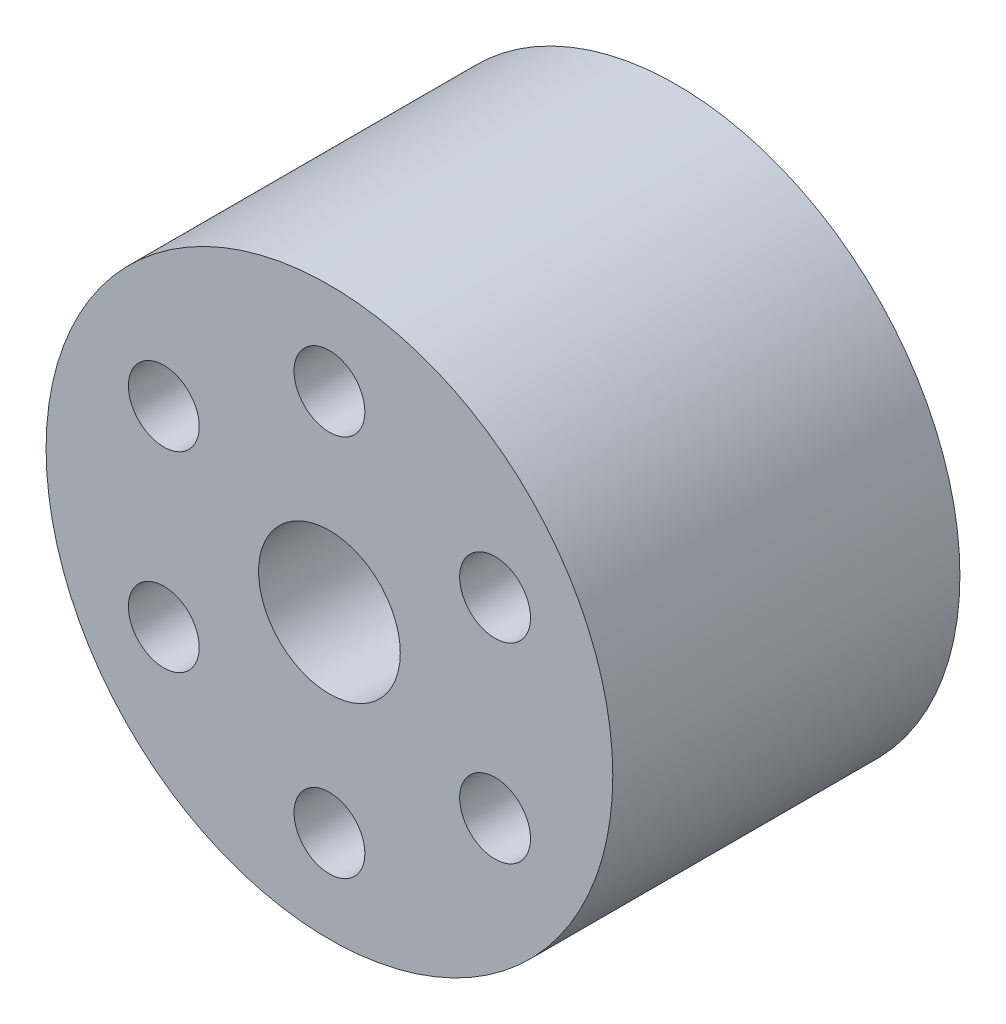
SolidWorks part; units mm, degrees
material "1060 합금"
ref_plane "정면" through (0, 0, 0) normal (0, 0, 1) x (1, 0, 0)
ref_plane "윗면" through (0, 0, 0) normal (0, 1, 0) x (1, 0, 0)
ref_plane "우측면" through (0, 0, 0) normal (1, 0, 0) x (0, 0, -1)
sketch "스케치1" plane through (0, 0, 0) normal (0, 0, 1) x (1, 0, 0)
  circle A0 centre (0, 0) radius 20
  dimension "D1" = 40
extrude "보스-돌출1" add sketch "스케치1" along normal blind 24.5
sketch "스케치2" plane through (0, 0, 24.5) normal (0, 0, 1) x (1, 0, 0)
  circle A0 centre (0, 0) radius 5
  dimension "D1" = 10
extrude "컷-돌출1" cut sketch "스케치2" against normal blind 10
sketch "스케치3" plane through (0, 0, 14.5) normal (0, 0, 1) x (1, 0, 0)
  circle A0 centre (0, 0) radius 4
  dimension "D1" = 8
extrude "컷-돌출2" cut sketch "스케치3" against normal through all
sketch "스케치4" plane through (0, 0, 24.5) normal (0, 0, 1) x (1, 0, 0)
  line L0 (0, 0) -> (0, 20) construction
  circle A0 centre (0, 0) radius 13.5 construction
  circle A1 centre (11.6913, 6.75) radius 2.5
  circle A2 centre (0, 0) radius 20 construction
  circle A3 centre (0, 13.5) radius 2.5
  circle A4 centre (11.6913, -6.75) radius 2.5
  circle A5 centre (0, -13.5) radius 2.5
  circle A6 centre (-11.6913, -6.75) radius 2.5
  circle A7 centre (-11.6913, 6.75) radius 2.5
  point P22 (0, 0)
  dimension "D1" = 27
  dimension "D2" = 6
  dimension "D4" = 5
extrude "컷-돌출3" cut sketch "스케치4" against normal blind 10
